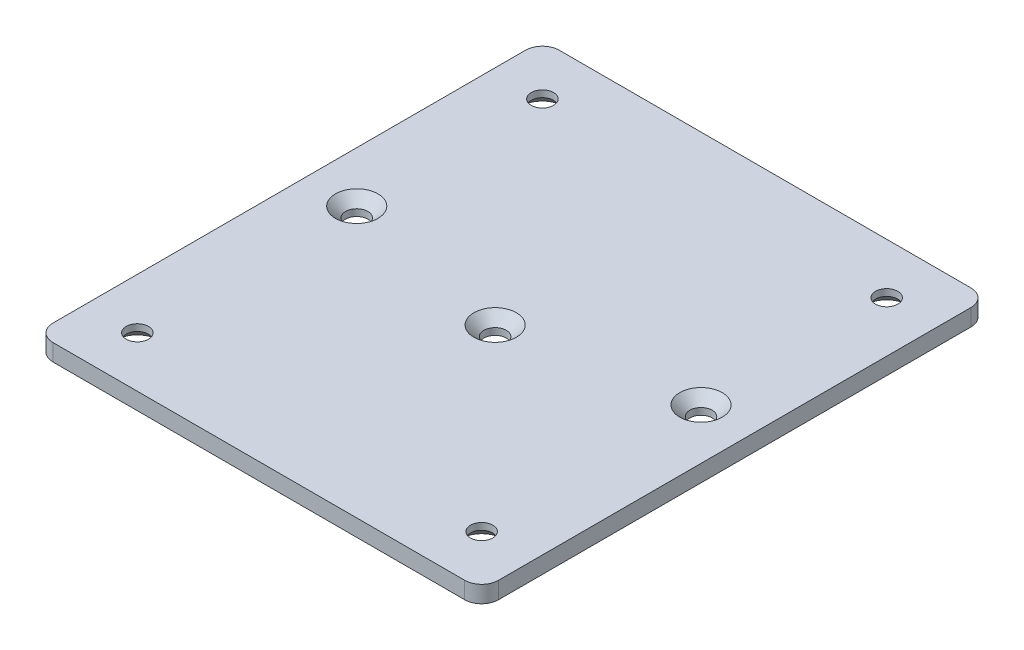
SolidWorks part; units mm, degrees
ref_plane "Front" through (0, 0, 0) normal (0, 0, 1) x (1, 0, 0)
ref_plane "Top" through (0, 0, 0) normal (0, 1, 0) x (1, 0, 0)
ref_plane "Right" through (0, 0, 0) normal (1, 0, 0) x (0, 0, -1)
sketch "Sketch1" plane through (0, 0, 0) normal (0, 1, 0) x (1, 0, 0)
  line L1 (0, 0) -> (132, 0)
  line L2 (0, 0) -> (0, 150)
  line L3 (0, 150) -> (132, 150)
  line L4 (132, 0) -> (132, 150)
  dimension "D1" = 132
  dimension "D2" = 150
extrude "Boss-Extrude1" add sketch "Sketch1" along normal blind 5
hole_wizard "CSK for M6 Flat Head Machine Screw1" positions "Sketch2" profile "Sketch3" countersink size "M6" standard "ANSI Metric"
sketch "Sketch2" plane through (0, 5, 0) normal (0, 1, 0) x (1, 0, 0)
  line L0 (117, 80) -> (15, 80) construction
  line L3 (132, 150) -> (0, 150) construction
  line L4 (66, 80) -> (66, 70) construction
  line L8 (0, 150) -> (0, 0) construction
  point P0 (15, 80)
  point P2 (66, 70)
  point P4 (117, 80)
  point P11 (66, 80)
  point P14 (66, 150)
  point P23 (66, 75)
  point P26 (0, 75)
  dimension "D1" = 10
  dimension "D2" = 102
sketch "Sketch3" plane through (15, 5, -80) normal (1, 0, 0) x (0, 0, 1)
  line L0 (0, 0) -> (0, 11.9828)
  line L1 (0, 11.9828) -> (3.3, 10)
  line L2 (3.3, 10) -> (3.3, 3)
  line L3 (3.3, 3) -> (6.3, 0)
  line L5 (6.3, 0) -> (0, 0)
  line L6 (-3.3, 3) -> (-6.3, 0) construction
  line L10 (0, 11.9828) -> (-3.3, 10) construction
  line L11 (0, -6.35) -> (0, 107.95) construction
  dimension "Hole Dia." = 6.6
  dimension "Hole Depth" = 10
  dimension "Near C'Sink Dia." = 12.6
  dimension "Near C'Sink Angle" = 90
  dimension "Drill Angle" = 118
hole_wizard "CSK for M6 Flat Head Machine Screw2" positions "Sketch4" profile "Sketch5" countersink size "M6" standard "ANSI Metric"
sketch "Sketch4" plane through (0, 0, 0) normal (0, -1, 0) x (-1, 0, 0)
  line L2 (-15, 15) -> (-117, 15) construction
  line L3 (-117, 15) -> (-117, 135) construction
  line L4 (-117, 135) -> (-15, 135) construction
  line L5 (-15, 135) -> (-15, 15) construction
  line L8 (0, 150) -> (0, 0) construction
  line L9 (-132, 150) -> (0, 150) construction
  point P0 (-15, 15)
  point P2 (-117, 15)
  point P4 (-117, 135)
  point P6 (-15, 135)
  point P19 (-15, 75)
  point P22 (0, 75)
  point P23 (-66, 135)
  point P26 (-66, 150)
  dimension "D1" = 120
  dimension "D2" = 102
sketch "Sketch5" plane through (15, 0, -15) normal (1, 0, 0) x (0, 0, -1)
  line L0 (0, 0) -> (0, 11.9828)
  line L1 (0, 11.9828) -> (3.3, 10)
  line L2 (3.3, 10) -> (3.3, 3)
  line L3 (3.3, 3) -> (6.3, 0)
  line L5 (6.3, 0) -> (0, 0)
  line L6 (-3.3, 3) -> (-6.3, 0) construction
  line L10 (0, 11.9828) -> (-3.3, 10) construction
  line L11 (0, -6.35) -> (0, 107.95) construction
  dimension "Hole Dia." = 6.6
  dimension "Hole Depth" = 10
  dimension "Near C'Sink Dia." = 12.6
  dimension "Near C'Sink Angle" = 90
  dimension "Drill Angle" = 118
fillet "Fillet1" radius 5 4 edges at (132, 2.5, -150) (132, 2.5, 0) (0, 2.5, 0) (0, 2.5, -150)
